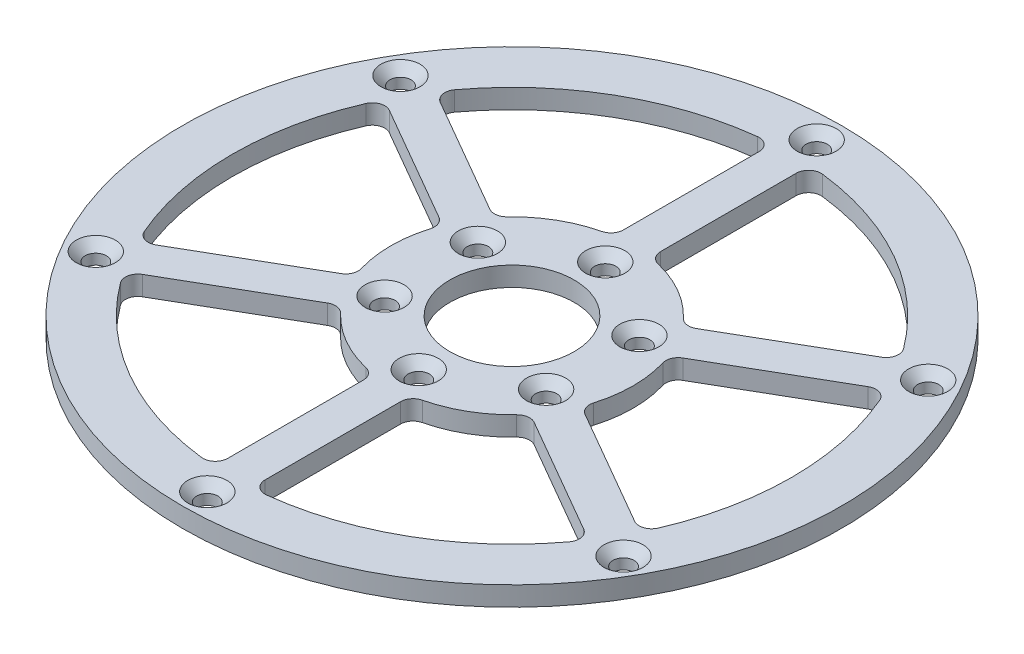
SolidWorks part; units mm, degrees
ref_plane "Front Plane" through (0, 0, 0) normal (0, 0, 1) x (1, 0, 0)
ref_plane "Top Plane" through (0, 0, 0) normal (0, 1, 0) x (1, 0, 0)
ref_plane "Right Plane" through (0, 0, 0) normal (1, 0, 0) x (0, 0, -1)
sketch "Sketch1" plane through (0, 0, 0) normal (0, 1, 0) x (1, 0, 0)
  circle A0 centre (0, 0) radius 53
  circle A1 centre (0, 0) radius 10
  dimension "D1" = 106
  dimension "42" = 20
extrude "Boss-Extrude1" add sketch "Sketch1" along normal blind 3.125
sketch "Sketch2" plane through (0, 3.125, 0) normal (0, 1, 0) x (1, 0, 0)
  line L0 (0, 0) -> (0, 53) construction
  line L2 (3, 42.7083) -> (3, 20.9105)
  line L3 (35.4865, 23.9522) -> (16.609, 13.0533)
  line L4 (38.4865, -18.7561) -> (19.609, -7.8572)
  line L5 (38.4865, 18.7561) -> (19.609, 7.8572)
  line L6 (3, -42.7083) -> (3, -20.9105)
  line L7 (35.4865, -23.9522) -> (16.609, -13.0533)
  line L8 (-35.4865, -23.9522) -> (-16.609, -13.0533)
  line L9 (-3, -42.7083) -> (-3, -20.9105)
  line L10 (-38.4865, 18.7561) -> (-19.609, 7.8572)
  line L11 (-38.4865, -18.7561) -> (-19.609, -7.8572)
  line L12 (-3, 42.7083) -> (-3, 20.9105)
  line L13 (-35.4865, 23.9522) -> (-16.609, 13.0533)
  line L14 (3, 40.9891) -> (-3, 40.9891) construction
  circle A0 centre (0, 0) radius 53 construction
  arc A1 (5.2326, 44.6947) -> (36.0905, 26.8789) centre (0, 0) cw
  arc A2 (4.5349, 18.9654) -> (14.157, 13.41) centre (0, 0) cw
  arc A3 (14.157, 13.41) -> (16.609, 13.0533) centre (15.609, 14.7854) ccw
  arc A4 (36.0905, 26.8789) -> (35.4865, 23.9522) centre (34.4865, 25.6843) cw
  arc A5 (3, 42.7083) -> (5.2326, 44.6947) centre (5, 42.7083) cw
  arc A6 (3, 20.9105) -> (4.5349, 18.9654) centre (5, 20.9105) ccw
  arc A7 (41.3231, -17.8158) -> (38.4865, -18.7561) centre (39.4865, -17.024) cw
  arc A8 (18.6919, -5.5554) -> (19.609, -7.8572) centre (20.609, -6.1251) ccw
  arc A9 (18.6919, 5.5554) -> (18.6919, -5.5554) centre (0, 0) cw
  arc A10 (19.609, 7.8572) -> (18.6919, 5.5554) centre (20.609, 6.1251) ccw
  arc A11 (38.4865, 18.7561) -> (41.3231, 17.8158) centre (39.4865, 17.024) cw
  arc A12 (41.3231, 17.8158) -> (41.3231, -17.8158) centre (0, 0) cw
  arc A13 (5.2326, -44.6947) -> (3, -42.7083) centre (5, -42.7083) cw
  arc A14 (4.5349, -18.9654) -> (3, -20.9105) centre (5, -20.9105) ccw
  arc A15 (14.157, -13.41) -> (4.5349, -18.9654) centre (0, 0) cw
  arc A16 (16.609, -13.0533) -> (14.157, -13.41) centre (15.609, -14.7854) ccw
  arc A17 (35.4865, -23.9522) -> (36.0905, -26.8789) centre (34.4865, -25.6843) cw
  arc A18 (36.0905, -26.8789) -> (5.2326, -44.6947) centre (0, 0) cw
  arc A19 (-36.0905, -26.8789) -> (-35.4865, -23.9522) centre (-34.4865, -25.6843) cw
  arc A20 (-14.157, -13.41) -> (-16.609, -13.0533) centre (-15.609, -14.7854) ccw
  arc A21 (-4.5349, -18.9654) -> (-14.157, -13.41) centre (0, 0) cw
  arc A22 (-3, -20.9105) -> (-4.5349, -18.9654) centre (-5, -20.9105) ccw
  arc A23 (-3, -42.7083) -> (-5.2326, -44.6947) centre (-5, -42.7083) cw
  arc A24 (-5.2326, -44.6947) -> (-36.0905, -26.8789) centre (0, 0) cw
  arc A25 (-41.3231, 17.8158) -> (-38.4865, 18.7561) centre (-39.4865, 17.024) cw
  arc A26 (-18.6919, 5.5554) -> (-19.609, 7.8572) centre (-20.609, 6.1251) ccw
  arc A27 (-18.6919, -5.5554) -> (-18.6919, 5.5554) centre (0, 0) cw
  arc A28 (-19.609, -7.8572) -> (-18.6919, -5.5554) centre (-20.609, -6.1251) ccw
  arc A29 (-38.4865, -18.7561) -> (-41.3231, -17.8158) centre (-39.4865, -17.024) cw
  arc A30 (-41.3231, -17.8158) -> (-41.3231, 17.8158) centre (0, 0) cw
  arc A31 (-5.2326, 44.6947) -> (-3, 42.7083) centre (-5, 42.7083) cw
  arc A32 (-4.5349, 18.9654) -> (-3, 20.9105) centre (-5, 20.9105) ccw
  arc A33 (-14.157, 13.41) -> (-4.5349, 18.9654) centre (0, 0) cw
  arc A34 (-16.609, 13.0533) -> (-14.157, 13.41) centre (-15.609, 14.7854) ccw
  arc A35 (-35.4865, 23.9522) -> (-36.0905, 26.8789) centre (-34.4865, 25.6843) cw
  arc A36 (-36.0905, 26.8789) -> (-5.2326, 44.6947) centre (0, 0) cw
  point P81 (0, 0)
  point P82 (0, 40.9891)
  dimension "D1" = 2
  dimension "D4" = 19.5
  dimension "D5" = 45
  dimension "D3" = 6
  dimension "D2" = 6
extrude "Cut-Extrude1" cut sketch "Sketch2" against normal through all
sketch "Sketch3" plane through (0, 3.125, 0) normal (0, 1, 0) x (1, 0, 0)
  circle A0 centre (0, 15) radius 1.6
  circle A1 centre (12.9904, 7.5) radius 1.6
  circle A2 centre (12.9904, -7.5) radius 1.6
  circle A3 centre (0, -15) radius 1.6
  circle A4 centre (-12.9904, -7.5) radius 1.6
  circle A5 centre (-12.9904, 7.5) radius 1.6
  point P9 (0, 0)
  dimension "D2" = 3.2
  dimension "D1" = 15
  dimension "D3" = 6
extrude "Cut-Extrude2" cut sketch "Sketch3" against normal through all
sketch "Sketch5" plane through (0, 3.125, 0) normal (0, 1, 0) x (1, 0, 0)
  line L0 (0, 0) -> (-42.4352, 24.5) construction
  line L1 (0, 0) -> (0, 33.0303) construction
  circle A0 centre (-42.4352, 24.5) radius 1.6
  circle A1 centre (0, 49) radius 1.6
  circle A2 centre (42.4352, 24.5) radius 1.6
  circle A3 centre (42.4352, -24.5) radius 1.6
  circle A4 centre (0, -49) radius 1.6
  circle A5 centre (-42.4352, -24.5) radius 1.6
  point P11 (0, 0)
  dimension "D3" = 3.2
  dimension "D1" = 60
  dimension "D2" = 49
  dimension "D4" = 6
extrude "Cut-Extrude3" cut sketch "Sketch5" against normal through all
hole_wizard "CSK for M3 Flat Head Machine Screw1" positions "3DSketch1" profile "Sketch4" countersink size "M3" standard "ANSI Metric"
sketch3d "3DSketch1"
  line L0 (-12.9904, 0, 7.5) -> (-12.9904, 3.125, 7.5) construction
  line L1 (-12.9904, 0, -7.5) -> (-12.9904, 3.125, -7.5) construction
  line L2 (0, 0, 15) -> (0, 3.125, 15) construction
  line L3 (-42.4352, 0, 24.5) -> (-42.4352, 3.125, 24.5) construction
  line L4 (0, 0, 49) -> (0, 3.125, 49) construction
  line L5 (42.4352, 0, 24.5) -> (42.4352, 3.125, 24.5) construction
  point P0 (0, 3.125, -15)
  point P3 (12.9904, 3.125, -7.5)
  point P6 (12.9904, 3.125, 7.5)
  point P9 (-56.0049, 63.9896, 0)
  point P11 (-42.4352, 3.125, -24.5)
  point P14 (0, 3.125, -49)
  point P17 (42.4352, 3.125, -24.5)
  point P20 (-12.9904, 3.125, 7.5)
  point P24 (-12.9904, 3.125, -7.5)
  point P28 (0, 3.125, 15)
  point P33 (-42.4352, 3.125, 24.5)
  point P37 (0, 3.125, 49)
  point P41 (42.4352, 3.125, 24.5)
sketch "Sketch4" plane through (0, 3.125, -15) normal (1, 0, 0) x (0, 0, 1)
  line L0 (0, 0) -> (0, 3.125)
  line L1 (0, 3.125) -> (1.7, 3.125)
  line L2 (1.7, 3.125) -> (1.7, 1.45)
  line L3 (1.7, 1.45) -> (3.15, 0)
  line L5 (3.15, 0) -> (0, 0)
  line L6 (-1.7, 1.45) -> (-3.15, 0) construction
  line L11 (0, -6.35) -> (0, 107.95) construction
  dimension "Thru Hole Dia." = 3.4
  dimension "Thru Hole Depth" = 3.125
  dimension "Near C'Sink Dia." = 6.3
  dimension "Near C'Sink Angle" = 90
